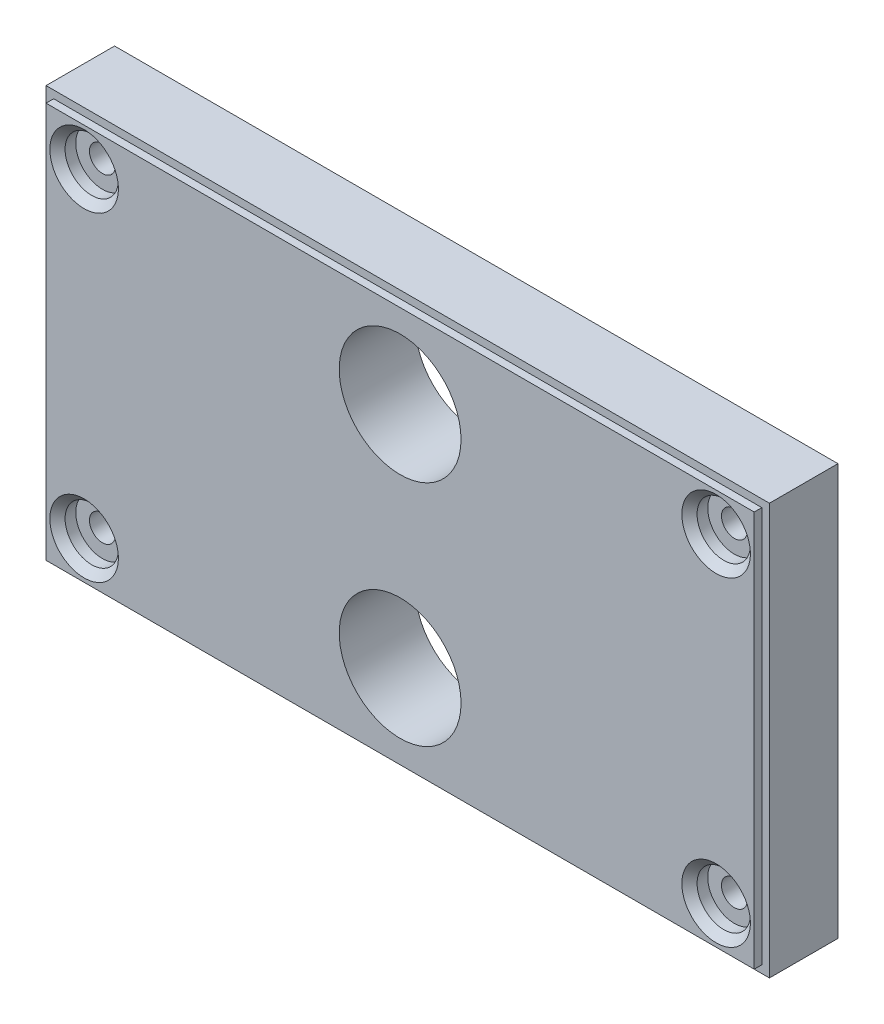
SolidWorks part; units mm, degrees
material "1060 Alloy"
ref_plane "Front Plane" through (0, 0, 0) normal (0, 0, 1) x (1, 0, 0)
ref_plane "Top Plane" through (0, 0, 0) normal (0, 1, 0) x (1, 0, 0)
ref_plane "Right Plane" through (0, 0, 0) normal (1, 0, 0) x (0, 0, -1)
sketch "Sketch1" plane through (0, 0, 0) normal (0, 0, 1) x (1, 0, 0)
  line L4 (-454.8517, 27) -> (-454.8517, -27)
  line L5 (-454.8517, -27) -> (-359.8517, -27)
  line L6 (-359.8517, -27) -> (-359.8517, 27)
  line L7 (-359.8517, 27) -> (-454.8517, 27)
  line L8 (-454.8517, 27) -> (-454.8517, -27)
  line L9 (-454.8517, -27) -> (-359.8517, -27)
  line L10 (-359.8517, -27) -> (-359.8517, 27)
  line L11 (-359.8517, 27) -> (-454.8517, 27)
  dimension "D1" = 0
extrude "Boss-Extrude1" add sketch "Sketch1" along normal up to surface (10 mm away)
sketch "Sketch2" plane through (0, 0, 10) normal (0, 0, 1) x (1, 0, 0)
  line L0 (-453.8517, 26) -> (-453.8517, -26)
  line L1 (-453.8517, -26) -> (-360.8517, -26)
  line L2 (-360.8517, -26) -> (-360.8517, 26)
  line L3 (-360.8517, 26) -> (-453.8517, 26)
  line L4 (-454.8517, 27) -> (-454.8517, -27)
  line L5 (-454.8517, -27) -> (-359.8517, -27)
  line L6 (-359.8517, -27) -> (-359.8517, 27)
  line L7 (-359.8517, 27) -> (-454.8517, 27)
  line L8 (-454.8517, 27) -> (-454.8517, -27)
  line L9 (-454.8517, -27) -> (-359.8517, -27)
  line L10 (-359.8517, -27) -> (-359.8517, 27)
  line L11 (-359.8517, 27) -> (-454.8517, 27)
  dimension "D1" = 0
  dimension "D2" = 1
extrude "Cut-Extrude1" cut sketch "Sketch2" against normal blind 1
hole_wizard "CBORE for M3 Pan Head Screw1" positions "3DSketch1" profile "Sketch3" counterbore size "M3" standard "ISO" end condition up to next
sketch3d "3DSketch1"
  point P0 (-448.8517, 21, 10)
  point P2 (-365.8517, 21, 10)
  point P4 (-365.8517, -21, 10)
  point P6 (-448.8517, -21, 10)
  dimension "D1" = 6
  dimension "D2" = 6
  dimension "D3" = 6
  dimension "D4" = 6
  dimension "D5" = 6
  dimension "D6" = 6
  dimension "D7" = 6
  dimension "D8" = 6
sketch "Sketch3" plane through (-448.8517, 21, 10) normal (1, 0, 0) x (0, -1, 0)
  line L0 (0, 0) -> (0, 10)
  line L1 (0, 10) -> (1.7, 10)
  line L3 (1.7, 10) -> (1.7, 2.4)
  line L4 (1.7, 2.4) -> (3.5, 2.4)
  line L5 (3.5, 2.4) -> (3.5, 0)
  line L7 (3.5, 0) -> (0, 0)
  line L11 (0, -6.35) -> (0, 107.95) construction
  dimension "Thru Hole Dia." = 3.4
  dimension "Thru Hole Depth" = 10
  dimension "C'Bore Dia." = 7
  dimension "C'Bore Depth" = 2.4
chamfer "Chamfer1" distance 1 angle 45 4 edges at (-362.3517, -21, 10) (-362.3517, 21, 10) (-445.3517, 21, 10) (-445.3517, -21, 10)
sketch "Sketch4" plane through (0, 0, 10) normal (0, 0, 1) x (1, 0, 0)
  line L0 (-454.8517, 0) -> (-359.8517, 0) construction
  line L1 (-454.8517, 27) -> (-454.8517, -27) construction
  line L2 (-359.8517, -27) -> (-359.8517, 27) construction
  line L3 (-407.3517, 27) -> (-407.3517, -27) construction
  line L4 (-359.8517, 27) -> (-454.8517, 27) construction
  line L5 (-454.8517, -27) -> (-359.8517, -27) construction
  circle A0 centre (-407.3517, 15) radius 8
  circle A1 centre (-407.3517, -15) radius 8
  dimension "D2" = 16
  dimension "D3" = 12
  dimension "D4" = 16
  dimension "D1" = 12
extrude "Cut-Extrude2" cut sketch "Sketch4" against normal blind 10
